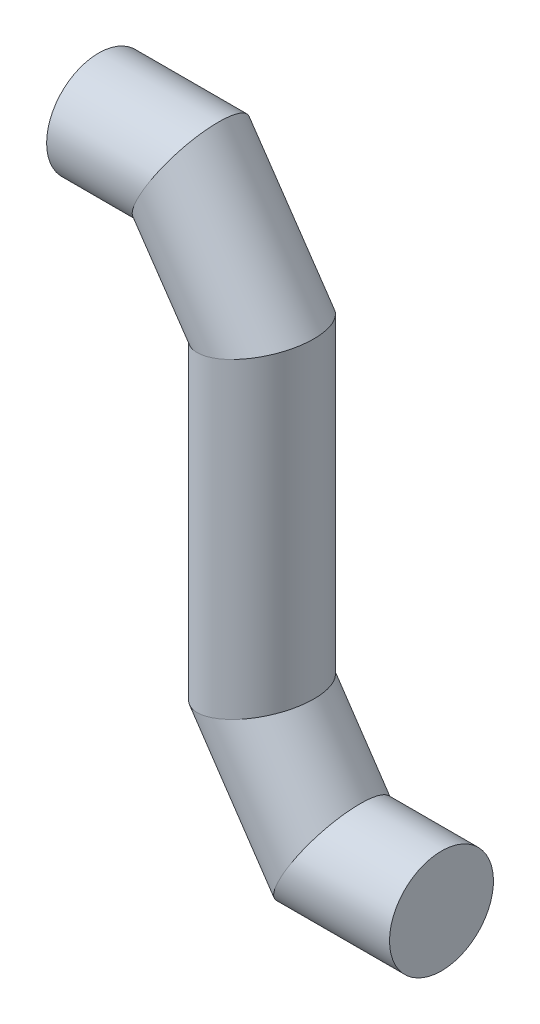
SolidWorks part; units mm, degrees
ref_plane "Front Plane" through (0, 0, 0) normal (0, 0, 1) x (1, 0, 0)
ref_plane "Top Plane" through (0, 0, 0) normal (0, 1, 0) x (1, 0, 0)
ref_plane "Right Plane" through (0, 0, 0) normal (1, 0, 0) x (0, 0, -1)
sketch "Sketch1" plane through (0, 0, 0) normal (0, 0, 1) x (1, 0, 0)
  line L0 (-15.7282, 25) -> (-6.8447, 25)
  line L1 (-6.8447, 25) -> (0, 15)
  line L2 (0, 15) -> (0, -15)
  line L3 (0, -15) -> (6.7718, -25)
  line L4 (6.7718, -25) -> (17.2718, -25)
  dimension "D1" = 30
  dimension "D2" = 10
  dimension "D3" = 10
  dimension "D4" = 33
sweep "Sweep1" add path "Sketch1" circular profile diameter 10 parameters "D3"=10
